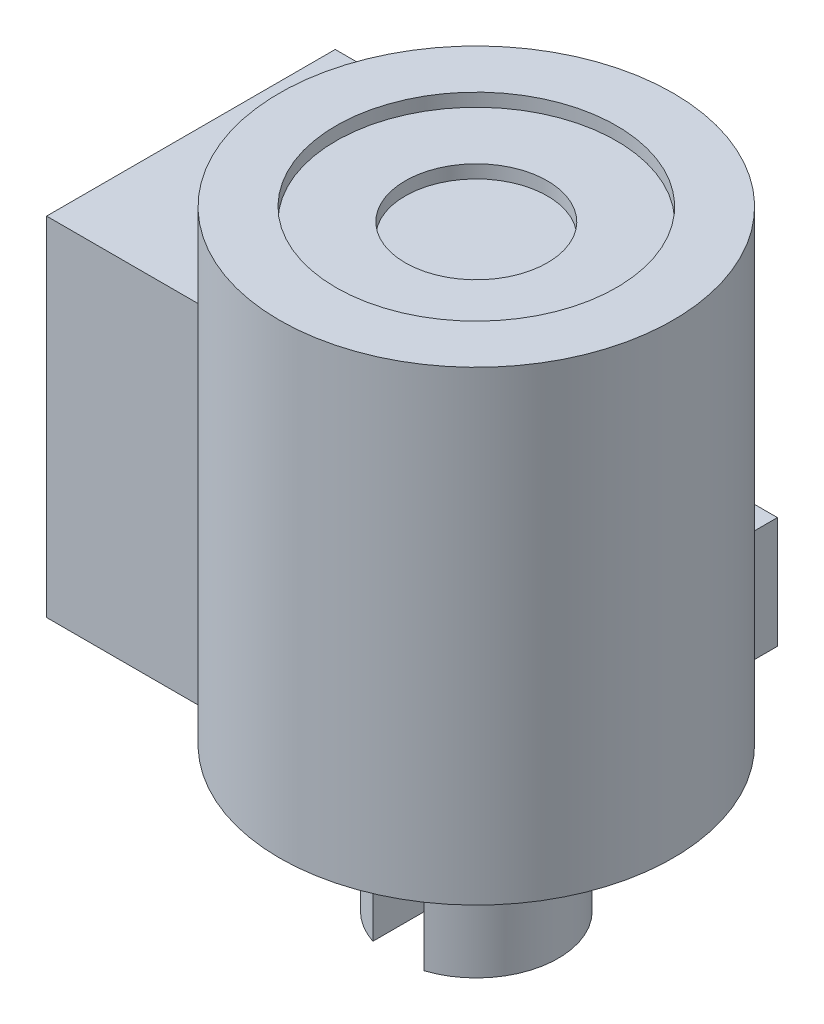
SolidWorks part; units mm, degrees
ref_plane "Plano frontal" through (0, 0, 0) normal (0, 0, 1) x (1, 0, 0)
ref_plane "Plano superior" through (0, 0, 0) normal (0, 1, 0) x (1, 0, 0)
ref_plane "Plano direito" through (0, 0, 0) normal (1, 0, 0) x (0, 0, -1)
sketch "Esboço1" plane through (0, 0, 0) normal (0, 1, 0) x (1, 0, 0)
  circle A0 centre (0, 0) radius 30
  dimension "D1" = 60
extrude "Ressalto-extrusão2" add sketch "Esboço1" along normal blind 10
sketch "Esboço3" plane through (0, 0, 0) normal (0, -1, 0) x (1, 0, 0)
  circle A0 centre (0, 0) radius 12.4948
extrude "Ressalto-extrusão3" add sketch "Esboço3" along normal blind 22
sketch "Esboço4" plane through (0, 10, 0) normal (0, 1, 0) x (1, 0, 0)
  circle A0 centre (0, 0) radius 18.3358
  circle A1 centre (0, 0) radius 30
  circle A2 centre (0, 0) radius 30
  dimension "D1" = 0
extrude "Ressalto-extrusão4" add sketch "Esboço4" along normal blind 51
sketch "Esboço5" plane through (0, 61, 0) normal (0, 1, 0) x (1, 0, 0)
  circle A0 centre (0, 0) radius 30 construction
  circle A1 centre (0, 0) radius 30
extrude "Ressalto-extrusão5" add sketch "Esboço5" along normal blind 10
sketch "Esboço6" plane through (0, 71, 0) normal (0, 1, 0) x (1, 0, 0)
  circle A0 centre (0, 0) radius 21.3823
extrude "Corte-extrusão1" cut sketch "Esboço6" against normal blind 2
sketch "Esboço7" plane through (0, 69, 0) normal (0, 1, 0) x (1, 0, 0)
  circle A0 centre (0, 0) radius 10.8336
extrude "Corte-extrusão2" cut sketch "Esboço7" against normal blind 2
sketch "Esboço8" plane through (0, -22, 0) normal (0, -1, 0) x (1, 0, 0)
  line L1 (-3.8922, -16.5213) -> (3.8922, -16.5213)
  line L2 (-3.8922, -16.5213) -> (-3.8922, 16.5213)
  line L3 (-3.8922, 16.5213) -> (3.8922, 16.5213)
  line L4 (3.8922, -16.5213) -> (3.8922, 16.5213)
  line L5 (-3.8922, -16.5213) -> (3.8922, 16.5213) construction
  line L6 (-3.8922, 16.5213) -> (3.8922, -16.5213) construction
  point P0 (0, 0)
extrude "Corte-extrusão3" cut sketch "Esboço8" against normal blind 17
sketch "Esboço10" plane through (0, 0, 0) normal (0, -1, 0) x (1, 0, 0)
  line L0 (0, -19.3883) -> (0, -50.2713) construction
  line L2 (-10, -30) -> (-10, -35.9017)
  line L3 (-10, -35.9017) -> (10, -35.9017)
  line L4 (10, -30) -> (10, -35.9017)
  line L5 (-10, -30) -> (-10, -28.2843)
  line L6 (10, -30) -> (10, -28.2843)
  circle A0 centre (0, 0) radius 30 construction
  circle A2 centre (0, 0) radius 30
  arc A3 (-10, -28.2843) -> (10, -28.2843) centre (0, 0) ccw
  point P9 (0, 0)
  point P11 (0, 0)
  point P12 (0, 0)
  dimension "D1" = 10
  dimension "D2" = 10
  dimension "D3" = 0
extrude "Ressalto-extrusão7" add sketch "Esboço10" against normal blind 17
sketch "Esboço11" plane through (0, 0, 0) normal (0, -1, 0) x (1, 0, 0)
  line L1 (8.7341, -35.0338) -> (-9.1773, -35.0338)
  line L2 (8.7341, -35.0338) -> (8.7341, -30.3036)
  line L3 (8.7341, -30.3036) -> (-9.1773, -30.3036)
  line L4 (-9.1773, -35.0338) -> (-9.1773, -30.3036)
extrude "Corte-extrusão4" cut sketch "Esboço11" against normal blind 14
ref_plane "Plano1" through (0, 30, 0) normal (0, 1, 0) x (1, 0, 0)
sketch "Esboço13" plane through (0, 30, 0) normal (0, 1, 0) x (1, 0, 0)
  line L0 (-30, 0) -> (-58.6719, 0) construction
  line L1 (-30, 22) -> (-43.5077, 22)
  line L3 (-30, -22) -> (-43.5077, -22)
  line L4 (-43.5077, 22) -> (-43.5077, -22)
  line L5 (-30, 22) -> (-20.3961, 22)
  line L6 (-30, -22) -> (-20.3961, -22)
  circle A0 centre (0, 0) radius 30 construction
  circle A2 centre (0, 0) radius 30
  arc A3 (-20.3961, -22) -> (-20.3961, 22) centre (0, 0) ccw
  point P9 (-20.3961, 22)
  point P12 (0, 0)
  point P13 (-20.2648, -22)
  point P14 (0, 0)
  point P15 (-20.339, 22)
  point P16 (0, 0)
  dimension "D1" = 22
  dimension "D2" = 22
  dimension "D3" = 0
extrude "Ressalto-extrusão9" add sketch "Esboço13" along normal blind 29 and the other way blind 24
